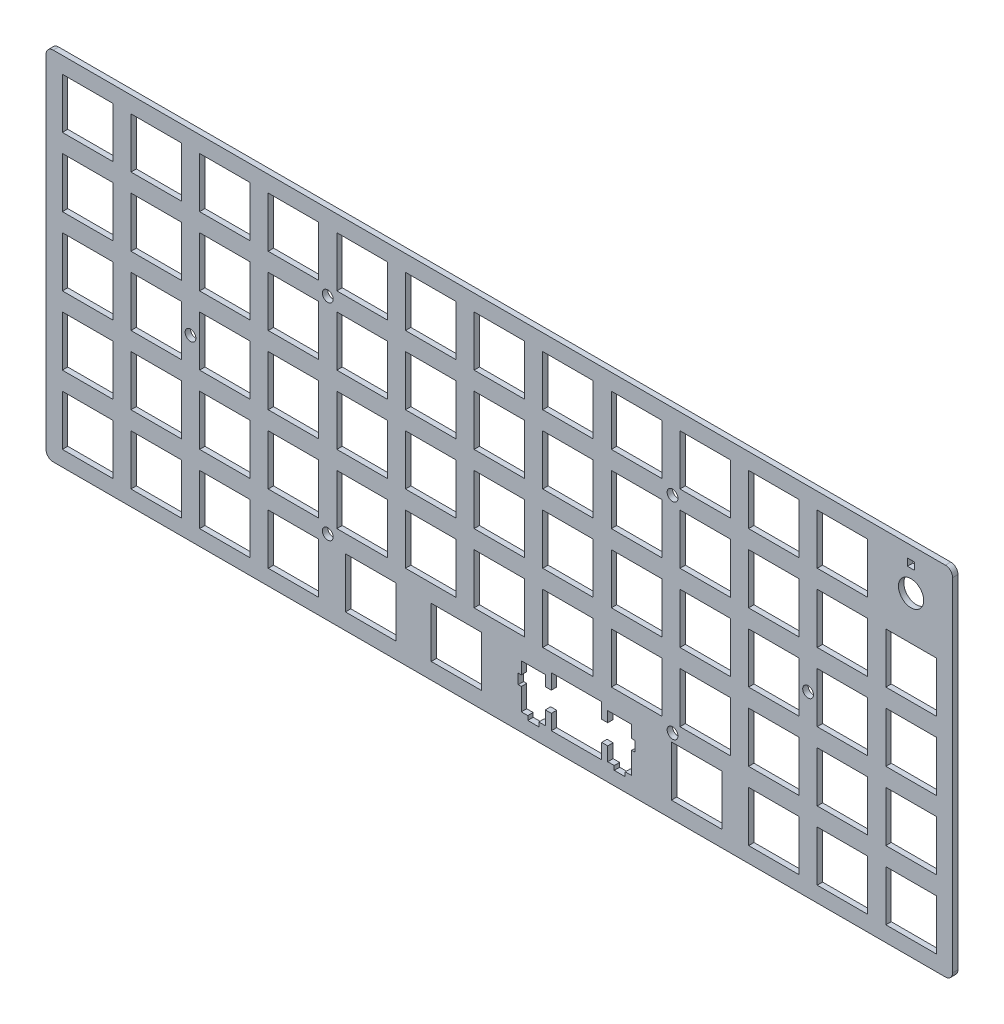
SolidWorks part; units mm, degrees
ref_plane "Front Plane" through (0, 0, 0) normal (0, 0, 1) x (1, 0, 0)
ref_plane "Top Plane" through (0, 0, 0) normal (0, 1, 0) x (1, 0, 0)
ref_plane "Right Plane" through (0, 0, 0) normal (1, 0, 0) x (0, 0, -1)
sketch "Sketch4" plane through (0, 0, 0) normal (0, 0, 1) x (1, 0, 0)
  line L0 (-121.2977, 30.9829) -> (-121.2977, 44.9783)
  line L1 (-121.2977, 30.9829) -> (-107.3023, 30.9829)
  line L2 (-123.825, 49.5056) -> (123.825, 49.5056)
  line L3 (-102.2477, 30.9829) -> (-102.2477, 44.9783)
  line L4 (-102.2477, 30.9829) -> (-88.2523, 30.9829)
  line L5 (-88.2523, 30.9829) -> (-88.2523, 44.9783)
  line L6 (-102.2477, 44.9783) -> (-88.2523, 44.9783)
  line L7 (-83.1977, 30.9829) -> (-83.1977, 44.9783)
  line L8 (-83.1977, 30.9829) -> (-69.2023, 30.9829)
  line L9 (-69.2023, 30.9829) -> (-69.2023, 44.9783)
  line L10 (-83.1977, 44.9783) -> (-69.2023, 44.9783)
  line L11 (-64.1477, 30.9829) -> (-64.1477, 44.9783)
  line L12 (-64.1477, 30.9829) -> (-50.1523, 30.9829)
  line L13 (-50.1523, 30.9829) -> (-50.1523, 44.9783)
  line L14 (-64.1477, 44.9783) -> (-50.1523, 44.9783)
  line L15 (-45.0977, 30.9829) -> (-45.0977, 44.9783)
  line L16 (-45.0977, 30.9829) -> (-31.1023, 30.9829)
  line L17 (-31.1023, 30.9829) -> (-31.1023, 44.9783)
  line L18 (-45.0977, 44.9783) -> (-31.1023, 44.9783)
  line L19 (-26.0477, 30.9829) -> (-26.0477, 44.9783)
  line L20 (-26.0477, 30.9829) -> (-12.0523, 30.9829)
  line L21 (-12.0523, 30.9829) -> (-12.0523, 44.9783)
  line L22 (-26.0477, 44.9783) -> (-12.0523, 44.9783)
  line L23 (-6.9977, 30.9829) -> (-6.9977, 44.9783)
  line L24 (-6.9977, 30.9829) -> (6.9977, 30.9829)
  line L25 (6.9977, 30.9829) -> (6.9977, 44.9783)
  line L26 (-6.9977, 44.9783) -> (6.9977, 44.9783)
  line L27 (12.0523, 30.9829) -> (12.0523, 44.9783)
  line L28 (12.0523, 30.9829) -> (26.0477, 30.9829)
  line L29 (26.0477, 30.9829) -> (26.0477, 44.9783)
  line L30 (12.0523, 44.9783) -> (26.0477, 44.9783)
  line L31 (31.1023, 30.9829) -> (31.1023, 44.9783)
  line L32 (31.1023, 30.9829) -> (45.0977, 30.9829)
  line L33 (45.0977, 30.9829) -> (45.0977, 44.9783)
  line L34 (31.1023, 44.9783) -> (45.0977, 44.9783)
  line L35 (50.1523, 30.9829) -> (50.1523, 44.9783)
  line L36 (50.1523, 30.9829) -> (64.1477, 30.9829)
  line L37 (64.1477, 30.9829) -> (64.1477, 44.9783)
  line L38 (50.1523, 44.9783) -> (64.1477, 44.9783)
  line L39 (69.2023, 30.9829) -> (69.2023, 44.9783)
  line L40 (69.2023, 30.9829) -> (83.1977, 30.9829)
  line L41 (83.1977, 30.9829) -> (83.1977, 44.9783)
  line L42 (69.2023, 44.9783) -> (83.1977, 44.9783)
  line L43 (88.2523, 30.9829) -> (88.2523, 44.9783)
  line L44 (88.2523, 30.9829) -> (102.2477, 30.9829)
  line L45 (102.2477, 30.9829) -> (102.2477, 44.9783)
  line L46 (88.2523, 44.9783) -> (102.2477, 44.9783)
  line L47 (-102.2477, 11.9329) -> (-102.2477, 25.9283)
  line L48 (-102.2477, 11.9329) -> (-88.2523, 11.9329)
  line L49 (-88.2523, 11.9329) -> (-88.2523, 25.9283)
  line L50 (-102.2477, 25.9283) -> (-88.2523, 25.9283)
  line L51 (-83.1977, 11.9329) -> (-83.1977, 25.9283)
  line L52 (-83.1977, 11.9329) -> (-69.2023, 11.9329)
  line L53 (-69.2023, 11.9329) -> (-69.2023, 25.9283)
  line L54 (-83.1977, 25.9283) -> (-69.2023, 25.9283)
  line L55 (-64.1477, 11.9329) -> (-64.1477, 25.9283)
  line L56 (-64.1477, 11.9329) -> (-50.1523, 11.9329)
  line L57 (-50.1523, 11.9329) -> (-50.1523, 25.9283)
  line L58 (-64.1477, 25.9283) -> (-50.1523, 25.9283)
  line L59 (-45.0977, 11.9329) -> (-45.0977, 25.9283)
  line L60 (-45.0977, 11.9329) -> (-31.1023, 11.9329)
  line L61 (-31.1023, 11.9329) -> (-31.1023, 25.9283)
  line L62 (-45.0977, 25.9283) -> (-31.1023, 25.9283)
  line L63 (-26.0477, 11.9329) -> (-26.0477, 25.9283)
  line L64 (-26.0477, 11.9329) -> (-12.0523, 11.9329)
  line L65 (-12.0523, 11.9329) -> (-12.0523, 25.9283)
  line L66 (-26.0477, 25.9283) -> (-12.0523, 25.9283)
  line L67 (-6.9977, 11.9329) -> (-6.9977, 25.9283)
  line L68 (-6.9977, 11.9329) -> (6.9977, 11.9329)
  line L69 (6.9977, 11.9329) -> (6.9977, 25.9283)
  line L70 (-6.9977, 25.9283) -> (6.9977, 25.9283)
  line L71 (12.0523, 11.9329) -> (12.0523, 25.9283)
  line L72 (12.0523, 11.9329) -> (26.0477, 11.9329)
  line L73 (26.0477, 11.9329) -> (26.0477, 25.9283)
  line L74 (12.0523, 25.9283) -> (26.0477, 25.9283)
  line L75 (31.1023, 11.9329) -> (31.1023, 25.9283)
  line L76 (31.1023, 11.9329) -> (45.0977, 11.9329)
  line L77 (45.0977, 11.9329) -> (45.0977, 25.9283)
  line L78 (31.1023, 25.9283) -> (45.0977, 25.9283)
  line L79 (50.1523, 11.9329) -> (50.1523, 25.9283)
  line L80 (50.1523, 11.9329) -> (64.1477, 11.9329)
  line L81 (64.1477, 11.9329) -> (64.1477, 25.9283)
  line L82 (50.1523, 25.9283) -> (64.1477, 25.9283)
  line L83 (69.2023, 11.9329) -> (69.2023, 25.9283)
  line L84 (69.2023, 11.9329) -> (83.1977, 11.9329)
  line L85 (83.1977, 11.9329) -> (83.1977, 25.9283)
  line L86 (69.2023, 25.9283) -> (83.1977, 25.9283)
  line L87 (88.2523, 11.9329) -> (88.2523, 25.9283)
  line L88 (88.2523, 11.9329) -> (102.2477, 11.9329)
  line L89 (102.2477, 11.9329) -> (102.2477, 25.9283)
  line L90 (88.2523, 25.9283) -> (102.2477, 25.9283)
  line L91 (107.3023, 11.9329) -> (107.3023, 25.9283)
  line L92 (107.3023, 11.9329) -> (121.2977, 11.9329)
  line L93 (121.2977, 11.9329) -> (121.2977, 25.9283)
  line L94 (107.3023, 25.9283) -> (121.2977, 25.9283)
  line L95 (-102.2477, -7.1171) -> (-102.2477, 6.8783)
  line L96 (-102.2477, -7.1171) -> (-88.2523, -7.1171)
  line L97 (-88.2523, -7.1171) -> (-88.2523, 6.8783)
  line L98 (-102.2477, 6.8783) -> (-88.2523, 6.8783)
  line L99 (-83.1977, -7.1171) -> (-83.1977, 6.8783)
  line L100 (-83.1977, -7.1171) -> (-69.2023, -7.1171)
  line L101 (-69.2023, -7.1171) -> (-69.2023, 6.8783)
  line L102 (-83.1977, 6.8783) -> (-69.2023, 6.8783)
  line L103 (-64.1477, -7.1171) -> (-64.1477, 6.8783)
  line L104 (-64.1477, -7.1171) -> (-50.1523, -7.1171)
  line L105 (-50.1523, -7.1171) -> (-50.1523, 6.8783)
  line L106 (-64.1477, 6.8783) -> (-50.1523, 6.8783)
  line L107 (-45.0977, -7.1171) -> (-45.0977, 6.8783)
  line L108 (-45.0977, -7.1171) -> (-31.1023, -7.1171)
  line L109 (-31.1023, -7.1171) -> (-31.1023, 6.8783)
  line L110 (-45.0977, 6.8783) -> (-31.1023, 6.8783)
  line L111 (-26.0477, -7.1171) -> (-26.0477, 6.8783)
  line L112 (-26.0477, -7.1171) -> (-12.0523, -7.1171)
  line L113 (-12.0523, -7.1171) -> (-12.0523, 6.8783)
  line L114 (-26.0477, 6.8783) -> (-12.0523, 6.8783)
  line L115 (-6.9977, -7.1171) -> (-6.9977, 6.8783)
  line L116 (-6.9977, -7.1171) -> (6.9977, -7.1171)
  line L117 (6.9977, -7.1171) -> (6.9977, 6.8783)
  line L118 (-6.9977, 6.8783) -> (6.9977, 6.8783)
  line L119 (12.0523, -7.1171) -> (12.0523, 6.8783)
  line L120 (12.0523, -7.1171) -> (26.0477, -7.1171)
  line L121 (26.0477, -7.1171) -> (26.0477, 6.8783)
  line L122 (12.0523, 6.8783) -> (26.0477, 6.8783)
  line L123 (31.1023, -7.1171) -> (31.1023, 6.8783)
  line L124 (31.1023, -7.1171) -> (45.0977, -7.1171)
  line L125 (45.0977, -7.1171) -> (45.0977, 6.8783)
  line L126 (31.1023, 6.8783) -> (45.0977, 6.8783)
  line L127 (50.1523, -7.1171) -> (50.1523, 6.8783)
  line L128 (50.1523, -7.1171) -> (64.1477, -7.1171)
  line L129 (64.1477, -7.1171) -> (64.1477, 6.8783)
  line L130 (50.1523, 6.8783) -> (64.1477, 6.8783)
  line L131 (69.2023, -7.1171) -> (69.2023, 6.8783)
  line L132 (69.2023, -7.1171) -> (83.1977, -7.1171)
  line L133 (83.1977, -7.1171) -> (83.1977, 6.8783)
  line L134 (69.2023, 6.8783) -> (83.1977, 6.8783)
  line L135 (88.2523, -7.1171) -> (88.2523, 6.8783)
  line L136 (88.2523, -7.1171) -> (102.2477, -7.1171)
  line L137 (102.2477, -7.1171) -> (102.2477, 6.8783)
  line L138 (88.2523, 6.8783) -> (102.2477, 6.8783)
  line L139 (107.3023, -7.1171) -> (107.3023, 6.8783)
  line L140 (107.3023, -7.1171) -> (121.2977, -7.1171)
  line L141 (121.2977, -7.1171) -> (121.2977, 6.8783)
  line L142 (107.3023, 6.8783) -> (121.2977, 6.8783)
  line L143 (-102.2477, -26.1671) -> (-102.2477, -12.1717)
  line L144 (-102.2477, -26.1671) -> (-88.2523, -26.1671)
  line L145 (-88.2523, -26.1671) -> (-88.2523, -12.1717)
  line L146 (-102.2477, -12.1717) -> (-88.2523, -12.1717)
  line L147 (-83.1977, -26.1671) -> (-83.1977, -12.1717)
  line L148 (-83.1977, -26.1671) -> (-69.2023, -26.1671)
  line L149 (-69.2023, -26.1671) -> (-69.2023, -12.1717)
  line L150 (-83.1977, -12.1717) -> (-69.2023, -12.1717)
  line L151 (-64.1477, -26.1671) -> (-64.1477, -12.1717)
  line L152 (-64.1477, -26.1671) -> (-50.1523, -26.1671)
  line L153 (-50.1523, -26.1671) -> (-50.1523, -12.1717)
  line L154 (-64.1477, -12.1717) -> (-50.1523, -12.1717)
  line L155 (-45.0977, -26.1671) -> (-45.0977, -12.1717)
  line L156 (-45.0977, -26.1671) -> (-31.1023, -26.1671)
  line L157 (-31.1023, -26.1671) -> (-31.1023, -12.1717)
  line L158 (-45.0977, -12.1717) -> (-31.1023, -12.1717)
  line L159 (-26.0477, -26.1671) -> (-26.0477, -12.1717)
  line L160 (-26.0477, -26.1671) -> (-12.0523, -26.1671)
  line L161 (-12.0523, -26.1671) -> (-12.0523, -12.1717)
  line L162 (-26.0477, -12.1717) -> (-12.0523, -12.1717)
  line L163 (-6.9977, -26.1671) -> (-6.9977, -12.1717)
  line L164 (-6.9977, -26.1671) -> (6.9977, -26.1671)
  line L165 (6.9977, -26.1671) -> (6.9977, -12.1717)
  line L166 (-6.9977, -12.1717) -> (6.9977, -12.1717)
  line L167 (12.0523, -26.1671) -> (12.0523, -12.1717)
  line L168 (12.0523, -26.1671) -> (26.0477, -26.1671)
  line L169 (26.0477, -26.1671) -> (26.0477, -12.1717)
  line L170 (12.0523, -12.1717) -> (26.0477, -12.1717)
  line L171 (31.1023, -26.1671) -> (31.1023, -12.1717)
  line L172 (31.1023, -26.1671) -> (45.0977, -26.1671)
  line L173 (45.0977, -26.1671) -> (45.0977, -12.1717)
  line L174 (31.1023, -12.1717) -> (45.0977, -12.1717)
  line L175 (50.1523, -26.1671) -> (50.1523, -12.1717)
  line L176 (50.1523, -26.1671) -> (64.1477, -26.1671)
  line L177 (64.1477, -26.1671) -> (64.1477, -12.1717)
  line L178 (50.1523, -12.1717) -> (64.1477, -12.1717)
  line L179 (69.2023, -26.1671) -> (69.2023, -12.1717)
  line L180 (69.2023, -26.1671) -> (83.1977, -26.1671)
  line L181 (83.1977, -26.1671) -> (83.1977, -12.1717)
  line L182 (69.2023, -12.1717) -> (83.1977, -12.1717)
  line L183 (88.2523, -26.1671) -> (88.2523, -12.1717)
  line L184 (88.2523, -26.1671) -> (102.2477, -26.1671)
  line L185 (102.2477, -26.1671) -> (102.2477, -12.1717)
  line L186 (88.2523, -12.1717) -> (102.2477, -12.1717)
  line L187 (107.3023, -26.1671) -> (107.3023, -12.1717)
  line L188 (107.3023, -26.1671) -> (121.2977, -26.1671)
  line L189 (121.2977, -26.1671) -> (121.2977, -12.1717)
  line L190 (107.3023, -12.1717) -> (121.2977, -12.1717)
  line L191 (-102.2477, -45.2171) -> (-102.2477, -31.2217)
  line L192 (-102.2477, -45.2171) -> (-88.2523, -45.2171)
  line L193 (-88.2523, -45.2171) -> (-88.2523, -31.2217)
  line L194 (-102.2477, -31.2217) -> (-88.2523, -31.2217)
  line L195 (-83.1977, -45.2171) -> (-83.1977, -31.2217)
  line L196 (-83.1977, -45.2171) -> (-69.2023, -45.2171)
  line L197 (-69.2023, -45.2171) -> (-69.2023, -31.2217)
  line L198 (-83.1977, -31.2217) -> (-69.2023, -31.2217)
  line L199 (-64.1477, -45.2171) -> (-64.1477, -31.2217)
  line L200 (-64.1477, -45.2171) -> (-50.1523, -45.2171)
  line L201 (-50.1523, -45.2171) -> (-50.1523, -31.2217)
  line L202 (-64.1477, -31.2217) -> (-50.1523, -31.2217)
  line L203 (69.2023, -45.2171) -> (69.2023, -31.2217)
  line L204 (69.2023, -45.2171) -> (83.1977, -45.2171)
  line L205 (83.1977, -45.2171) -> (83.1977, -31.2217)
  line L206 (69.2023, -31.2217) -> (83.1977, -31.2217)
  line L207 (88.2523, -45.2171) -> (88.2523, -31.2217)
  line L208 (88.2523, -45.2171) -> (102.2477, -45.2171)
  line L209 (102.2477, -45.2171) -> (102.2477, -31.2217)
  line L210 (88.2523, -31.2217) -> (102.2477, -31.2217)
  line L211 (107.3023, -45.2171) -> (107.3023, -31.2217)
  line L212 (107.3023, -45.2171) -> (121.2977, -45.2171)
  line L213 (121.2977, -45.2171) -> (121.2977, -31.2217)
  line L214 (107.3023, -31.2217) -> (121.2977, -31.2217)
  line L215 (-121.2977, 11.9329) -> (-121.2977, 25.9283)
  line L216 (-121.2977, 11.9329) -> (-107.3023, 11.9329)
  line L217 (-107.3023, 11.9329) -> (-107.3023, 25.9283)
  line L218 (-121.2977, 25.9283) -> (-107.3023, 25.9283)
  line L219 (-121.2977, -7.1171) -> (-121.2977, 6.8783)
  line L220 (-121.2977, -7.1171) -> (-107.3023, -7.1171)
  line L221 (-107.3023, -7.1171) -> (-107.3023, 6.8783)
  line L222 (-121.2977, 6.8783) -> (-107.3023, 6.8783)
  line L223 (-121.2977, -26.1671) -> (-121.2977, -12.1717)
  line L224 (-121.2977, -26.1671) -> (-107.3023, -26.1671)
  line L225 (-107.3023, -26.1671) -> (-107.3023, -12.1717)
  line L226 (-121.2977, -12.1717) -> (-107.3023, -12.1717)
  line L227 (-121.2977, -45.2171) -> (-121.2977, -31.2217)
  line L228 (-121.2977, -45.2171) -> (-107.3023, -45.2171)
  line L229 (-107.3023, -45.2171) -> (-107.3023, -31.2217)
  line L230 (-121.2977, -31.2217) -> (-107.3023, -31.2217)
  line L231 (-42.7164, -45.0082) -> (-28.721, -45.0082)
  line L232 (-107.3023, 30.9829) -> (-107.3023, 44.9783)
  line L233 (-121.2977, 44.9783) -> (-107.3023, 44.9783)
  line L234 (-42.7164, -45.0082) -> (-42.7164, -31.0128)
  line L235 (-42.7164, -31.0128) -> (-28.721, -31.0128)
  line L236 (-28.721, -45.0082) -> (-28.721, -31.0128)
  line L245 (-125.825, 47.5056) -> (-125.825, -47.5056)
  line L248 (-18.904, -45.0082) -> (-4.9086, -45.0082)
  line L249 (-18.904, -45.0082) -> (-18.904, -31.0128)
  line L250 (-18.904, -31.0128) -> (-4.9086, -31.0128)
  line L251 (-4.9086, -45.0082) -> (-4.9086, -31.0128)
  line L254 (47.7711, -45.0082) -> (61.7665, -45.0082)
  line L255 (47.7711, -45.0082) -> (47.7711, -31.0128)
  line L256 (47.7711, -31.0128) -> (61.7665, -31.0128)
  line L257 (61.7665, -45.0082) -> (61.7665, -31.0128)
  line L260 (-121.2977, 44.9783) -> (-107.3023, 30.9829) construction
  line L261 (-121.2977, 30.9829) -> (-107.3023, 44.9783) construction
  line L262 (113.3, 43.9783) -> (115.3, 43.9783)
  line L263 (113.3, 43.9783) -> (113.3, 45.9783)
  line L264 (113.3, 45.9783) -> (115.3, 45.9783)
  line L265 (115.3, 43.9783) -> (115.3, 45.9783)
  line L268 (-123.825, -49.5056) -> (123.825, -49.5056)
  line L269 (125.825, 47.5056) -> (125.825, -47.5056)
  line L270 (-125.825, 49.5056) -> (125.825, -49.5056) construction
  line L271 (-125.825, -49.5056) -> (125.825, 49.5056) construction
  line L272 (14.4462, -31.0255) -> (28.4162, -31.0255)
  line L273 (14.4462, -44.9955) -> (28.4162, -44.9955)
  line L274 (28.4162, -31.0255) -> (28.4162, -35.2436)
  line L275 (30.1038, -32.3209) -> (36.7586, -32.3209)
  line L276 (30.1038, -32.3209) -> (30.1038, -35.2436)
  line L277 (30.1038, -44.6145) -> (31.9072, -44.6145)
  line L278 (36.7586, -32.3209) -> (36.7586, -35.7245)
  line L279 (31.9072, -44.6145) -> (31.9072, -45.7829)
  line L280 (36.7586, -35.7245) -> (37.6222, -35.7245)
  line L281 (36.7586, -38.5185) -> (37.6222, -38.5185)
  line L282 (37.6222, -35.7245) -> (37.6222, -38.5185)
  line L283 (31.9072, -45.7829) -> (34.9552, -45.7829)
  line L284 (34.9552, -44.6145) -> (34.9552, -45.7829)
  line L285 (30.1038, -40.8039) -> (28.4162, -40.8039)
  line L286 (30.1038, -35.2436) -> (28.4162, -35.2436)
  line L287 (30.1038, -40.8039) -> (30.1038, -44.6145)
  line L288 (28.4162, -40.8039) -> (28.4162, -44.9955)
  line L289 (36.7586, -38.5185) -> (36.7586, -44.6145)
  line L290 (34.9552, -44.6145) -> (36.7586, -44.6145)
  line L291 (10.9552, -44.6145) -> (10.9552, -45.7829)
  line L292 (12.7586, -32.3209) -> (12.7586, -35.2436)
  line L293 (12.7586, -32.3209) -> (6.1038, -32.3209)
  line L294 (6.1038, -32.3209) -> (6.1038, -35.7245)
  line L295 (6.1038, -35.7245) -> (5.2402, -35.7245)
  line L296 (5.2402, -35.7245) -> (5.2402, -38.5185)
  line L297 (6.1038, -38.5185) -> (5.2402, -38.5185)
  line L298 (6.1038, -38.5185) -> (6.1038, -44.6145)
  line L299 (7.9072, -44.6145) -> (7.9072, -45.7829)
  line L300 (7.9072, -44.6145) -> (6.1038, -44.6145)
  line L301 (10.9552, -45.7829) -> (7.9072, -45.7829)
  line L302 (12.7586, -44.6145) -> (10.9552, -44.6145)
  line L303 (12.7586, -40.8039) -> (12.7586, -44.6145)
  line L304 (12.7586, -40.8039) -> (14.4462, -40.8039)
  line L305 (12.7586, -35.2436) -> (14.4462, -35.2436)
  line L306 (14.4462, -31.0255) -> (14.4462, -35.2436)
  line L307 (14.4462, -40.8039) -> (14.4462, -44.9955)
  circle A0 centre (114.3, 37.9806) radius 3.5
  arc A1 (-125.825, -47.5056) -> (-123.825, -49.5056) centre (-123.825, -47.5056) ccw
  arc A2 (123.825, -49.5056) -> (125.825, -47.5056) centre (123.825, -47.5056) ccw
  arc A3 (125.825, 47.5056) -> (123.825, 49.5056) centre (123.825, 47.5056) ccw
  arc A4 (-123.825, 49.5056) -> (-125.825, 47.5056) centre (-123.825, 47.5056) ccw
  circle A5 centre (-85.725, 0) radius 1.5
  circle A6 centre (85.725, 0) radius 1.5
  circle A7 centre (48.0908, -28.6944) radius 1.5
  circle A8 centre (48.0908, 28.4556) radius 1.5
  circle A9 centre (-47.625, 28.4556) radius 1.5
  circle A10 centre (-47.625, -28.6944) radius 1.5
  point P272 (0, 0)
  dimension "D1" = 3
  dimension "D2" = 3
  dimension "D3" = 3
extrude "Boss-Extrude2" add sketch "Sketch4" along normal blind 1.5
